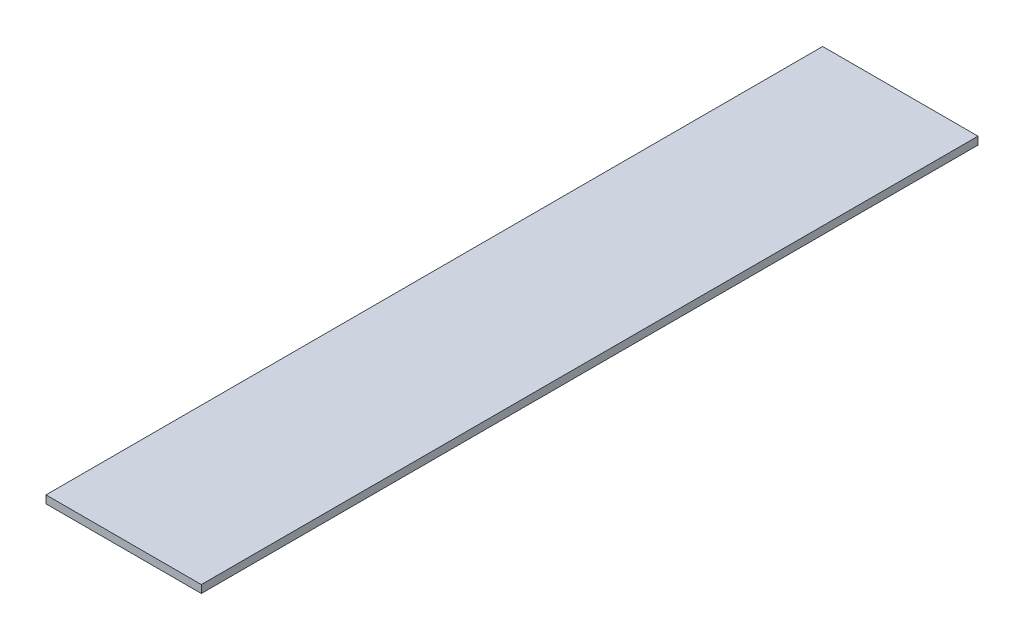
SolidWorks part; units mm, degrees
material "铸造合金钢"
ref_plane "前视基准面" through (0, 0, 0) normal (0, 0, 1) x (1, 0, 0)
ref_plane "上视基准面" through (0, 0, 0) normal (0, 1, 0) x (1, 0, 0)
ref_plane "右视基准面" through (0, 0, 0) normal (1, 0, 0) x (0, 0, -1)
sketch "草图2" plane through (0, 0, 0) normal (0, 0, 1) x (1, 0, 0)
  line L1 (0, 0) -> (200, 0)
  line L2 (0, 0) -> (0, -10)
  line L3 (0, -10) -> (200, -10)
  line L4 (200, 0) -> (200, -10)
extrude "凸台-拉伸1" add sketch "草图2" along normal blind 1000 contours L1 L4 L3 L2
